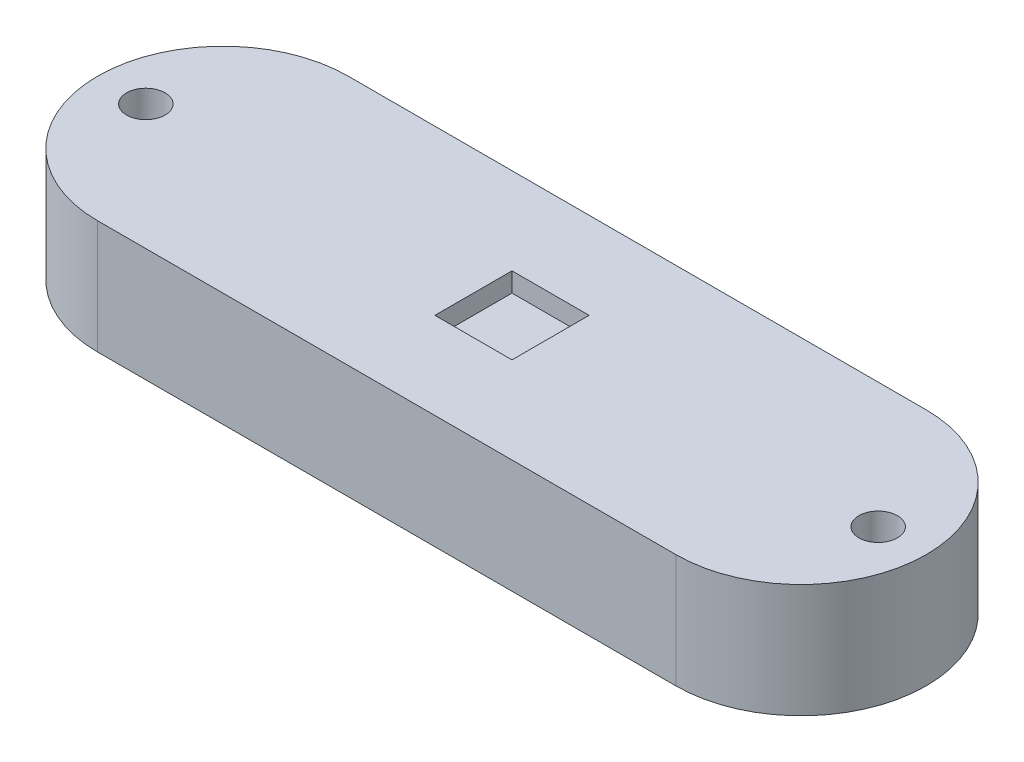
SolidWorks part; units mm, degrees
ref_plane "Front Plane" through (0, 0, 0) normal (0, 0, 1) x (1, 0, 0)
ref_plane "Top Plane" through (0, 0, 0) normal (0, 1, 0) x (1, 0, 0)
ref_plane "Right Plane" through (0, 0, 0) normal (1, 0, 0) x (0, 0, -1)
sketch "Sketch1" plane through (0, 0, 0) normal (0, 1, 0) x (1, 0, 0)
  line L5 (-15, 6.5) -> (15, 6.5)
  line L7 (-15, -6.5) -> (15, -6.5)
  line L9 (-18.3749, 5.5552) -> (18.3749, -5.5552) construction
  line L10 (-18.3749, -5.5552) -> (18.3749, 5.5552) construction
  arc A2 (15, -6.5) -> (15, 6.5) centre (15, 0) ccw
  arc A3 (-15, 6.5) -> (-15, -6.5) centre (-15, 0) ccw
  point P0 (0, 0)
extrude "Boss-Extrude1" add sketch "Sketch1" along normal blind 5.9
sketch "Sketch2" plane through (0, 5.9, 0) normal (0, 1, 0) x (1, 0, 0)
  line L0 (-19, 0) -> (19, 0) construction
  circle A0 centre (-19, 0) radius 1
  circle A1 centre (19, 0) radius 1
  point P4 (0, 0)
extrude "Cut-Extrude1" cut sketch "Sketch2" against normal blind 5.9
sketch "Sketch3" plane through (0, 5.9, 0) normal (0, 1, 0) x (1, 0, 0)
  line L1 (-2, -2) -> (2, -2)
  line L2 (-2, -2) -> (-2, 2)
  line L3 (-2, 2) -> (2, 2)
  line L4 (2, -2) -> (2, 2)
  line L5 (-2, -2) -> (2, 2) construction
  line L6 (-2, 2) -> (2, -2) construction
  point P0 (0, 0)
extrude "Cut-Extrude2" cut sketch "Sketch3" against normal blind 1
sketch "Sketch4" plane through (0, 0, 0) normal (0, -1, 0) x (1, 0, 0)
  line L1 (5.9346, -2.2806) -> (13.9346, -2.2806)
  line L2 (5.9346, -2.2806) -> (5.9346, 2.7194)
  line L3 (5.9346, 2.7194) -> (13.9346, 2.7194)
  line L4 (13.9346, -2.2806) -> (13.9346, 2.7194)
  line L5 (5.9346, -2.2806) -> (13.9346, 2.7194) construction
  line L6 (5.9346, 2.7194) -> (13.9346, -2.2806) construction
  point P0 (9.9346, 0.2194)
extrude "Boss-Extrude2" add sketch "Sketch4" along normal blind 1.95
sketch "Sketch5" plane through (0, 0, 0) normal (0, 1, 0) x (1, 0, 0)
  line L0 (177.9308, 452.5416) -> (967.2642, 452.5416) construction
